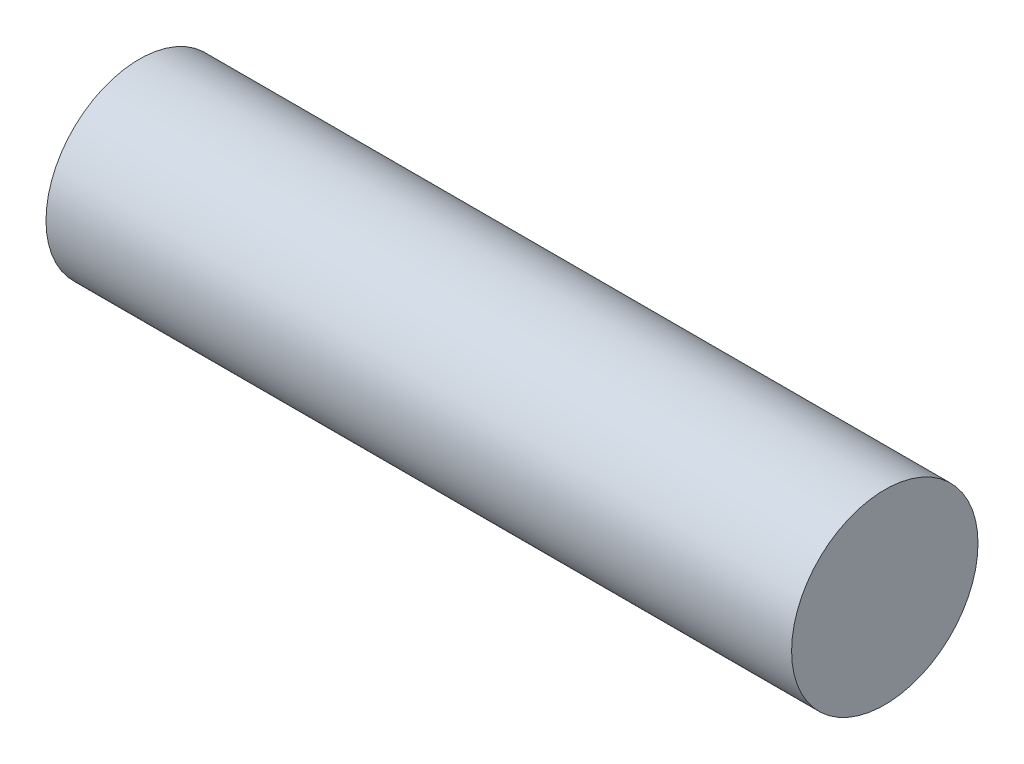
SolidWorks part; units mm, degrees
ref_plane "Front Plane" through (0, 0, 0) normal (0, 0, 1) x (1, 0, 0)
ref_plane "Top Plane" through (0, 0, 0) normal (0, 1, 0) x (1, 0, 0)
ref_plane "Right Plane" through (0, 0, 0) normal (1, 0, 0) x (0, 0, -1)
sketch "Sketch1" plane through (0, 0, 0) normal (1, 0, 0) x (0, 0, -1)
  circle A0 centre (0, 0) radius 3.175
  dimension "D1" = 6.35
extrude "Boss-Extrude1" add sketch "Sketch1" along normal mid plane 25.4
